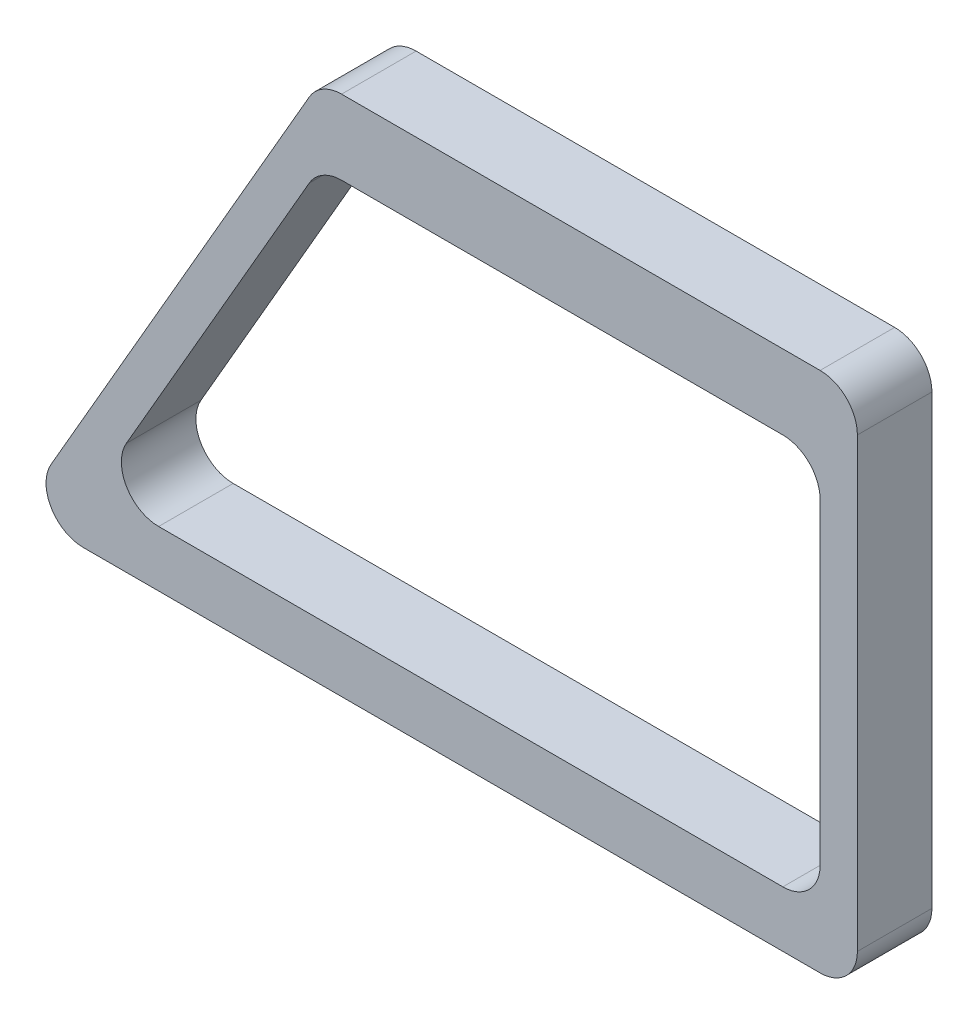
SolidWorks part; units mm, degrees
ref_plane "Front Plane" through (0, 0, 0) normal (0, 0, 1) x (1, 0, 0)
ref_plane "Top Plane" through (0, 0, 0) normal (0, 1, 0) x (1, 0, 0)
ref_plane "Right Plane" through (0, 0, 0) normal (1, 0, 0) x (0, 0, -1)
sketch "Sketch1" plane through (0, 0, 0) normal (0, 0, 1) x (1, 0, 0)
  line L0 (-36.6497, -46.3731) -> (125.0084, 233.6269)
  line L1 (-186.6497, -46.3731) -> (413.3503, -46.3731)
  line L2 (-186.6497, -46.3731) -> (-186.6497, 233.6269)
  line L3 (-186.6497, 233.6269) -> (413.3503, 233.6269)
  line L4 (413.3503, -46.3731) -> (413.3503, 233.6269)
  line L5 (78.8203, 193.6269) -> (-48.1967, -26.3731)
  line L6 (-166.6497, -26.3731) -> (-48.1967, -26.3731)
  line L7 (-166.6497, -26.3731) -> (-166.6497, 193.6269)
  line L8 (-166.6497, 193.6269) -> (78.8203, 193.6269)
  line L9 (393.3503, -16.3731) -> (393.3503, 193.6269)
  line L10 (125.0084, 193.6269) -> (393.3503, 193.6269)
  line L12 (3.7648, -16.3731) -> (125.0084, 193.6269)
  line L13 (393.3503, -16.3731) -> (3.7648, -16.3731)
  point P0 (0, 0)
  point P9 (0, 0)
  dimension "D1" = 20
  dimension "D2" = 600
  dimension "D3" = 450
  dimension "D4" = 20
  dimension "D5" = 40
  dimension "D6" = 20
  dimension "D7" = 20
  dimension "D8" = 20
  dimension "D9" = 280
  dimension "D10" = 30
extrude "Boss-Extrude1" add sketch "Sketch1" along normal blind 40
sketch "Sketch3" plane through (0, 0, 0) normal (0, 0, -1) x (-1, 0, 0)
  circle A0 centre (-180.9235, 226.1269) radius 2.5
  circle A2 centre (-200.9235, 211.1269) radius 2.5
  circle A3 centre (-220.9235, 226.1269) radius 2.5
  dimension "D2" = 5
  dimension "D5" = 5
  dimension "D7" = 5
extrude "Cut-Extrude1" cut sketch "Sketch3" against normal blind 10
ref_plane "Plane2" through (264.9553, 0, 0) normal (1, 0, 0) x (0, 0, -1)
mirror "Mirror1" about plane through (264.9553, 0, 0) normal (1, 0, 0) of "Cut-Extrude1"
fillet "Fillet3" radius 20 8 edges at (393.3503, -16.3731, 20) (3.7648, -16.3731, 20) (393.3503, 193.6269, 20) (125.0084, 193.6269, 20) (413.3503, 233.6269, 20) (413.3503, -46.3731, 20) (-36.6497, -46.3731, 20) (125.0084, 233.6269, 20)
